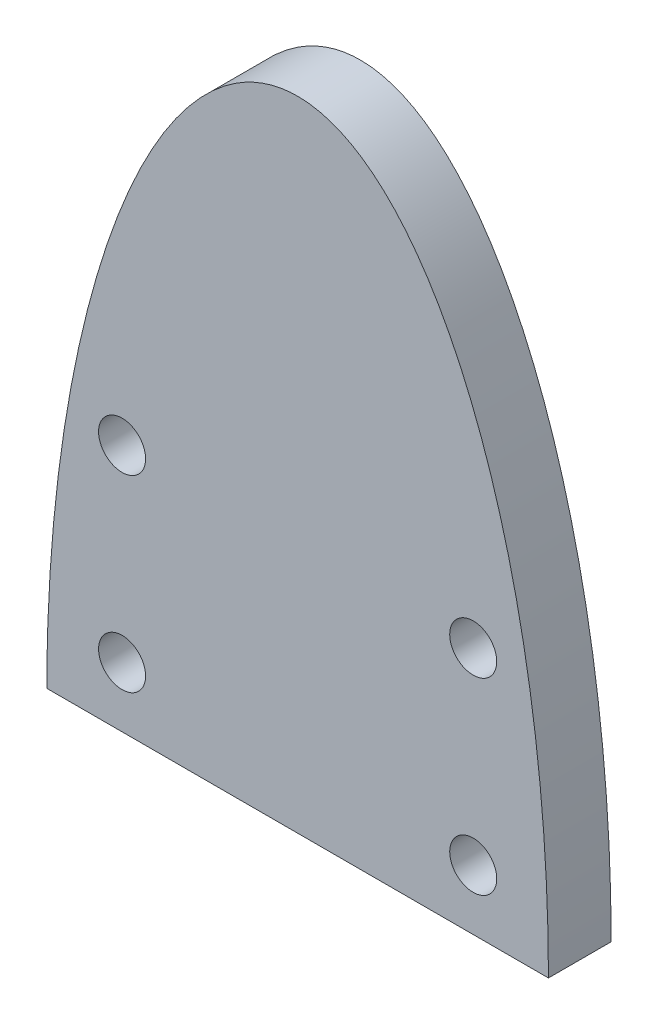
SolidWorks part; units mm, degrees
ref_plane "Front Plane" through (0, 0, 0) normal (0, 0, 1) x (1, 0, 0)
ref_plane "Top Plane" through (0, 0, 0) normal (0, 1, 0) x (1, 0, 0)
ref_plane "Right Plane" through (0, 0, 0) normal (1, 0, 0) x (0, 0, -1)
sketch "Sketch1" plane through (0, 0, 0) normal (0, 0, 1) x (1, 0, 0)
  line L0 (0, 0) -> (101.6, 0)
  ellipse E0 centre (50.8, 0) end of major axis (50.8, 129.286) minor radius 50.8 (101.6, 0) -> (0, 0) ccw
  dimension "D1" = 101.6
  dimension "D2" = 129.286
extrude "Boss-Extrude1" add sketch "Sketch1" along normal blind 12.7 contours E0 L0
sketch "Sketch2" plane through (0, 0, 0) normal (0, 0, -1) x (-1, 0, 0)
  line L0 (-50.8, 0) -> (-50.8, 181.515) construction
  line L1 (0, 0) -> (-101.6, 0) construction
  circle A0 centre (-86.36, 50.2666) radius 4.7625
  circle A1 centre (-86.36, 12.1666) radius 4.7625
  circle A2 centre (-15.24, 50.2666) radius 4.7625
  circle A3 centre (-15.24, 12.1666) radius 4.7625
  dimension "D1" = 9.525
  dimension "D2" = 38.1
  dimension "D3" = 35.56
  dimension "D4" = 35.56
  dimension "D5" = 12.1666
extrude "Cut-Extrude1" cut sketch "Sketch2" against normal blind 12.7
